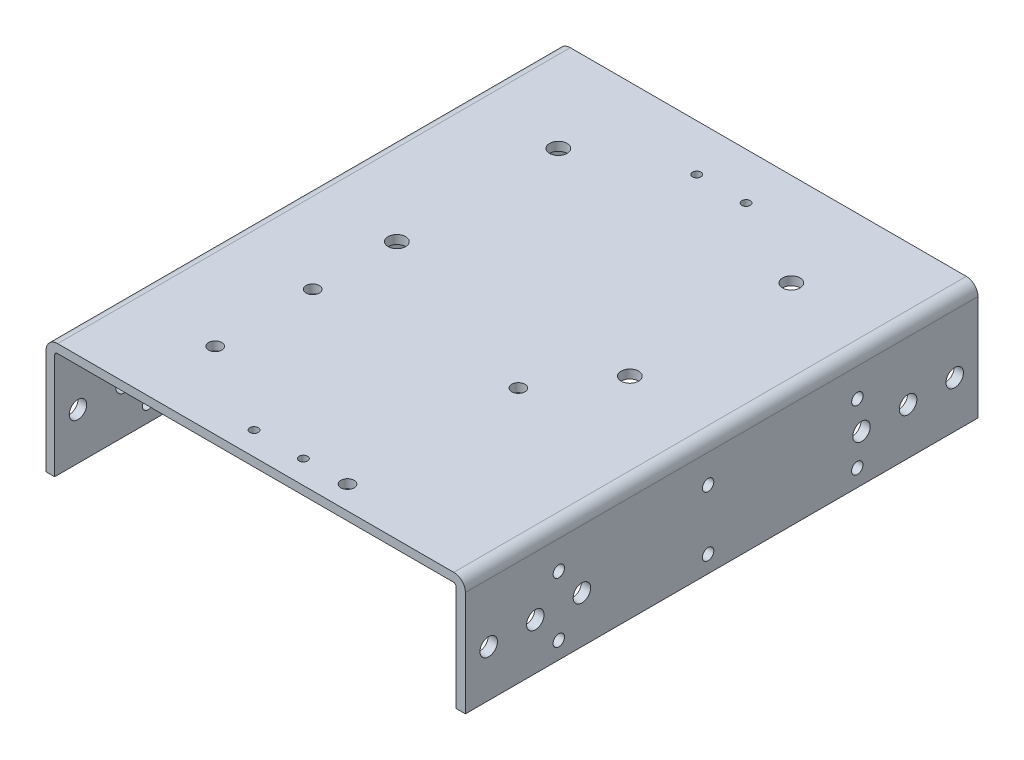
SolidWorks part; units mm, degrees
ref_plane "Front Plane" through (0, 0, 0) normal (0, 0, 1) x (1, 0, 0)
ref_plane "Top Plane" through (0, 0, 0) normal (0, 1, 0) x (1, 0, 0)
ref_plane "Right Plane" through (0, 0, 0) normal (1, 0, 0) x (0, 0, -1)
ref_plane "Plane1" through (0, -31.8365, 0) normal (0, -1, 0) x (1, 0, 0)
sketch "Sketch1" plane through (0, -31.8365, 0) normal (0, -1, 0) x (1, 0, 0)
  line L0 (142.9512, 19.05) -> (28.6512, 19.05)
  line L1 (28.6512, 19.05) -> (28.6512, -120.65)
  line L2 (28.6512, -120.65) -> (142.9512, -120.65)
  line L3 (142.9512, -120.65) -> (142.9512, 19.05)
  dimension "D1" = 139.7
  dimension "D2" = 114.3
extrude "Boss-Extrude1" add sketch "Sketch1" against normal blind 31.8365
sketch "Sketch2" plane through (0, 0, -120.65) normal (0, 0, -1) x (-1, 0, 0)
  line L0 (-140.4366, -31.8365) -> (-31.0134, -31.8365)
  line L1 (-31.0134, -31.8365) -> (-31.0134, -2.3622)
  line L2 (-31.0134, -2.3622) -> (-140.4366, -2.3622)
  line L3 (-140.4366, -2.3622) -> (-140.4366, -31.8365)
extrude "Cut-Extrude1" cut sketch "Sketch2" against normal through all
hole_wizard "M4 Clearance Hole1" positions "Sketch4" profile "Sketch3" hole size "M4" standard "ANSI Metric"
sketch "Sketch4" plane through (0, 0, 0) normal (0, 1, 0) x (1, 0, 0)
  line L1 (28.6512, 120.65) -> (142.9512, 120.65) construction
  point P0 (117.475, 95.25)
  point P1 (53.975, 51.2467)
  point P2 (117.475, 51.2467)
  point P3 (53.975, 95.25)
  dimension "D1" = 63.5
  dimension "D2" = 44.0033
  dimension "D3" = 25.4
sketch "Sketch3" plane through (117.475, 0, -95.25) normal (1, 0, 0) x (0, 0, 1)
  line L0 (0, 0) -> (0, 31.8365)
  line L1 (0, 31.8365) -> (2.3812, 31.8365)
  line L2 (2.3812, 31.8365) -> (2.3812, 0)
  line L5 (2.3812, 0) -> (0, 0)
  line L11 (0, -6.35) -> (0, 107.95) construction
  dimension "Thru Hole Dia." = 4.7625
  dimension "Thru Hole Depth" = 31.8365
hole_wizard "M3 Clearance Hole1" positions "Sketch6" profile "Sketch5" hole size "M3" standard "ANSI Metric" end condition through all
sketch "Sketch6" plane through (0, 0, 0) normal (0, 1, 0) x (1, 0, 0)
  point P0 (104.4702, -12.7)
  point P1 (53.7489, 28.5166)
  point P2 (105.0849, 33.2435)
  point P3 (53.9189, 1.7771)
  dimension "D1" = 26.74
  dimension "D2" = 50.5513
sketch "Sketch5" plane through (104.4702, 0, 12.7) normal (1, 0, 0) x (0, 0, 1)
  line L0 (0, 0) -> (0, 31.8365)
  line L1 (0, 31.8365) -> (1.7996, 31.8365)
  line L2 (1.7996, 31.8365) -> (1.7996, 0)
  line L5 (1.7996, 0) -> (0, 0)
  line L11 (0, -6.35) -> (0, 107.95) construction
  dimension "Thru Hole Dia." = 3.5992
  dimension "Thru Hole Depth" = 31.8365
hole_wizard "M2 Clearance Hole1" positions "Sketch8" profile "Sketch7" hole size "M2" standard "ANSI Metric"
sketch "Sketch8" plane through (0, 0, 0) normal (0, 1, 0) x (1, 0, 0)
  line L0 (28.6512, 120.65) -> (142.9512, 120.65) construction
  line L1 (142.9512, -19.05) -> (28.6512, -19.05) construction
  point P0 (92.456, 107.95)
  point P1 (78.994, 107.95)
  point P4 (78.994, -12.7)
  point P6 (92.456, -12.7)
  dimension "D1" = 13.462
  dimension "D2" = 12.7
  dimension "D3" = 13.462
  dimension "D4" = 6.35
sketch "Sketch7" plane through (92.456, 0, -107.95) normal (1, 0, 0) x (0, 0, 1)
  line L0 (0, 0) -> (0, 31.8365)
  line L1 (0, 31.8365) -> (1.143, 31.8365)
  line L2 (1.143, 31.8365) -> (1.143, 0)
  line L5 (1.143, 0) -> (0, 0)
  line L11 (0, -6.35) -> (0, 107.95) construction
  dimension "Thru Hole Dia." = 2.286
  dimension "Thru Hole Depth" = 31.8365
hole_wizard "M4 Clearance Hole2" positions "Sketch10" profile "Sketch9" hole size "M4" standard "ANSI Metric" end condition through all
sketch "Sketch10" plane through (142.9512, 0, 0) normal (1, 0, 0) x (0, 0, -1)
  line L0 (-19.05, 0) -> (-19.05, -31.8365) construction
  line L1 (120.65, 0) -> (120.65, -31.8365) construction
  point P0 (12.7, -19.1365)
  point P1 (-12.7, -19.1365)
  point P2 (0, -19.1365)
  point P3 (88.9, -19.1365)
  point P5 (101.6, -19.1365)
  point P7 (114.3, -19.1365)
  dimension "D1" = 12.7
  dimension "D2" = 12.7
  dimension "D3" = 6.35
  dimension "D4" = 6.35
  dimension "D5" = 12.7
  dimension "D6" = 12.7
sketch "Sketch9" plane through (142.9512, -19.1365, -12.7) normal (0, 1, 0) x (0, 0, -1)
  line L0 (0, 0) -> (0, 114.3)
  line L1 (0, 114.3) -> (2.3812, 114.3)
  line L2 (2.3812, 114.3) -> (2.3812, 0)
  line L5 (2.3812, 0) -> (0, 0)
  line L11 (0, -6.35) -> (0, 107.95) construction
  dimension "Thru Hole Dia." = 4.7625
  dimension "Thru Hole Depth" = 114.3
hole_wizard "Ø3.1 (3.1) Diameter Hole1" positions "Sketch12" profile "Sketch11" hole size "Ø3.1" standard "ANSI Metric" end condition through all
sketch "Sketch12" plane through (142.9512, 0, 0) normal (1, 0, 0) x (0, 0, -1)
  point P0 (47.0932, -27.1815)
  point P1 (87.75, -27.1815)
  point P2 (47.0932, -10.8815)
  point P3 (87.7764, -10.8815)
  point P4 (6.41, -10.8815)
  point P6 (6.41, -27.1815)
  dimension "D1" = 40.6832
  dimension "D2" = 16.3
  dimension "D3" = 40.6832
sketch "Sketch11" plane through (142.9512, -27.1815, -47.0932) normal (0, 1, 0) x (0, 0, -1)
  line L0 (0, 0) -> (0, 114.3)
  line L1 (0, 114.3) -> (1.55, 114.3)
  line L2 (1.55, 114.3) -> (1.55, 0)
  line L5 (1.55, 0) -> (0, 0)
  line L11 (0, -6.35) -> (0, 107.95) construction
  dimension "Thru Hole Dia." = 3.1
  dimension "Thru Hole Depth" = 114.3
hole_wizard "M4 Clearance Hole3" positions "Sketch14" profile "Sketch13" hole size "M4" standard "ANSI Metric"
sketch "Sketch14" plane through (31.0134, 0, 0) normal (1, 0, 0) x (0, 0, -1)
  point P0 (12.7, -19.1365)
  point P1 (-12.7, -19.1365)
  point P2 (0, -19.1365)
sketch "Sketch13" plane through (31.0134, -19.1365, -12.7) normal (0, 1, 0) x (0, 0, -1)
  line L0 (0, 0) -> (0, 2.3622)
  line L1 (0, 2.3622) -> (2.3812, 2.3622)
  line L2 (2.3812, 2.3622) -> (2.3812, 0)
  line L5 (2.3812, 0) -> (0, 0)
  line L11 (0, -6.35) -> (0, 107.95) construction
  dimension "Thru Hole Dia." = 4.7625
  dimension "Thru Hole Depth" = 2.3622
hole_wizard "Ø3.1 (3.1) Diameter Hole2" positions "Sketch16" profile "Sketch15" hole size "Ø3.1" standard "ANSI Metric"
sketch "Sketch16" plane through (31.0134, 0, 0) normal (1, 0, 0) x (0, 0, -1)
  point P0 (47.05, -27.1815)
  point P1 (87.75, -27.1815)
  point P2 (47.05, -10.8815)
  point P3 (87.75, -10.8815)
sketch "Sketch15" plane through (31.0134, -27.1815, -47.05) normal (0, 1, 0) x (0, 0, -1)
  line L0 (0, 0) -> (0, 2.3622)
  line L1 (0, 2.3622) -> (1.55, 2.3622)
  line L2 (1.55, 2.3622) -> (1.55, 0)
  line L5 (1.55, 0) -> (0, 0)
  line L11 (0, -6.35) -> (0, 107.95) construction
  dimension "Thru Hole Dia." = 3.1
  dimension "Thru Hole Depth" = 2.3622
fillet "Fillet1" radius 0.7366 2 edges at (140.4366, -2.3622, -50.8) (31.0134, -2.3622, -50.8)
fillet "Fillet2" radius 3.175 2 edges at (142.9512, 0, -50.8) (28.6512, 0, -50.8)
